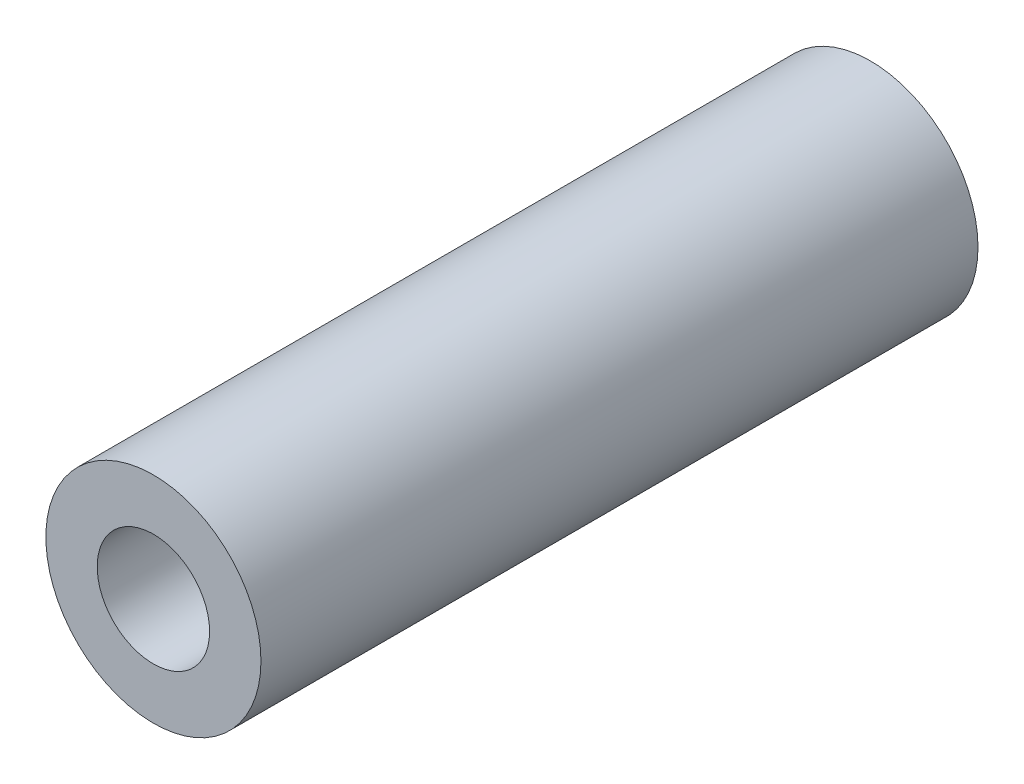
SolidWorks part; units mm, degrees
material "6061-T6 (SS)"
ref_plane "Front Plane" through (0, 0, 0) normal (0, 0, 1) x (1, 0, 0)
ref_plane "Top Plane" through (0, 0, 0) normal (0, 1, 0) x (1, 0, 0)
ref_plane "Right Plane" through (0, 0, 0) normal (1, 0, 0) x (0, 0, -1)
sketch "Sketch1" plane through (0, 0, 0) normal (0, 0, 1) x (1, 0, 0)
  circle A0 centre (0, 0) radius 4.7625
  circle A1 centre (0, 0) radius 2.4892
  dimension "D1" = 9.525
  dimension "D2" = 4.9784
extrude "Boss-Extrude1" add sketch "Sketch1" along normal mid plane 31.75
